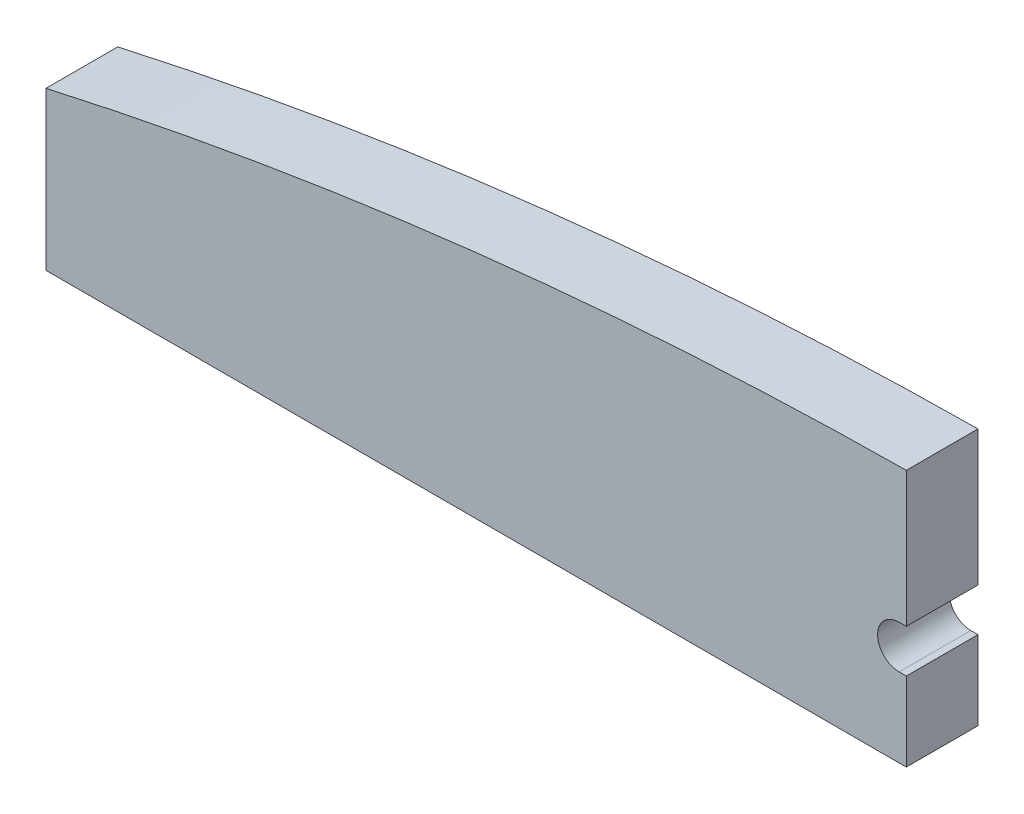
SolidWorks part; units mm, degrees
ref_plane "Спереди" through (0, 0, 0) normal (0, 0, 1) x (1, 0, 0)
ref_plane "Сверху" through (0, 0, 0) normal (0, 1, 0) x (1, 0, 0)
ref_plane "Справа" through (0, 0, 0) normal (1, 0, 0) x (0, 0, -1)
sketch "Эскиз1" plane through (0, 0, 0) normal (0, 0, 1) x (1, 0, 0)
  line L0 (-265.8511, 235.1138) -> (-265.1833, 241.0765) construction
  line L1 (-62.5, 4.0625) -> (-6, 4.0625)
  line L2 (-6, 4.0625) -> (-6, 0) construction
  line L3 (-62.5, 4.0625) -> (-62.5, 15.0625)
  line L4 (0, -11.9127) -> (0, 30.0636) construction
  line L5 (6, 4.0625) -> (6, 0) construction
  line L6 (62.5, 4.0625) -> (6, 4.0625) construction
  line L7 (62.5, 4.0625) -> (62.5, 15.0625)
  line L8 (-6, 4.0625) -> (6, 4.0625) construction
  line L9 (-3, 55.1234) -> (-3, 6.2714) construction
  line L10 (-2.5, 4.0625) -> (-2.5, 9.5625)
  line L11 (-3, 12.5625) -> (-2.5, 12.5625)
  line L12 (-3, 9.5625) -> (-2.5, 9.5625)
  line L13 (-2.5, 12.5625) -> (-2.5, 21.989)
  line L14 (-6, 4.0625) -> (-2.5, 4.0625)
  line L15 (-2.5, 20.2055) -> (-2.5, 23.4322) construction
  circle A0 centre (0, 0) radius 2.45 construction
  arc A1 (-6, 0) -> (6, 0) centre (0, 0) ccw construction
  circle A2 centre (0, 16.5) radius 2.45 construction
  arc A3 (-62.5, 15.0625) -> (-2.5, 21.989) centre (0, -263) cw
  arc A4 (62.5, 15.0625) -> (0, 22) centre (0, -263) ccw construction
  arc A5 (-3, 12.5625) -> (-3, 9.5625) centre (-3, 11.0625) ccw
  dimension "D2" = 4.9
  dimension "D3" = 6
  dimension "D4" = 125
  dimension "D5" = 22
  dimension "D7" = 285
  dimension "D8" = 4.9
  dimension "D10" = 3
  dimension "D1" = 6
  dimension "D6" = 11
  dimension "D9" = 16.5
  dimension "D11" = 3
  dimension "D12" = 7
  dimension "D13" = 2.5
extrude "Бобышка-Вытянуть1" add sketch "Эскиз1" along normal blind 5 contours A5 L11 L13 A3 L3 L1 L14 L10 L12
